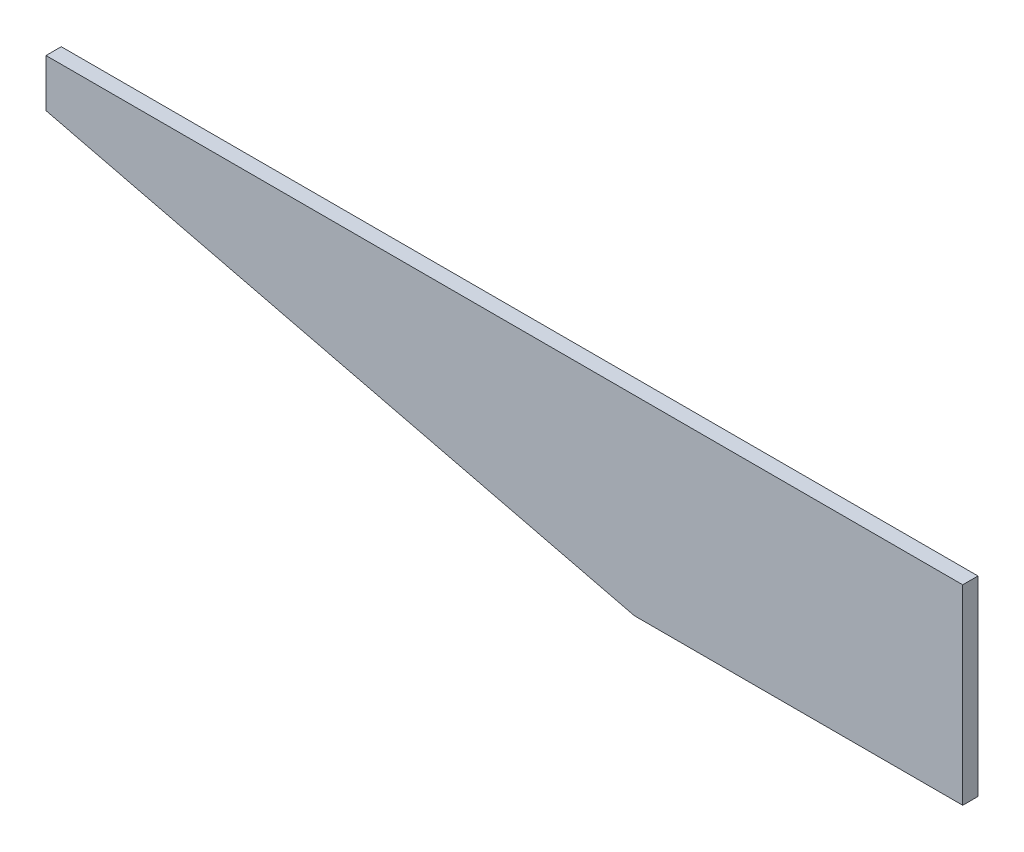
SolidWorks part; units mm, degrees
ref_plane "Plan de face" through (0, 0, 0) normal (0, 0, 1) x (1, 0, 0)
ref_plane "Plan de dessus" through (0, 0, 0) normal (0, 1, 0) x (1, 0, 0)
ref_plane "Plan de droite" through (0, 0, 0) normal (1, 0, 0) x (0, 0, -1)
sketch "Esquisse1" plane through (0, 0, 0) normal (0, 0, 1) x (1, 0, 0)
  line L0 (-600, 0) -> (0, 0) construction
  line L1 (-600, 0) -> (0, 0)
  line L2 (0, 0) -> (0, -125)
  line L3 (0, -125) -> (-215, -125)
  line L4 (-215, -125) -> (-600, -31.25)
  line L5 (-600, -31.25) -> (-600, 0)
  point P3 (0, 0)
  point P6 (0, 0)
  dimension "D1" = 125
  dimension "D2" = 215
  dimension "D3" = 31.25
extrude "Boss.-Extru.1" add sketch "Esquisse1" against normal blind 10
